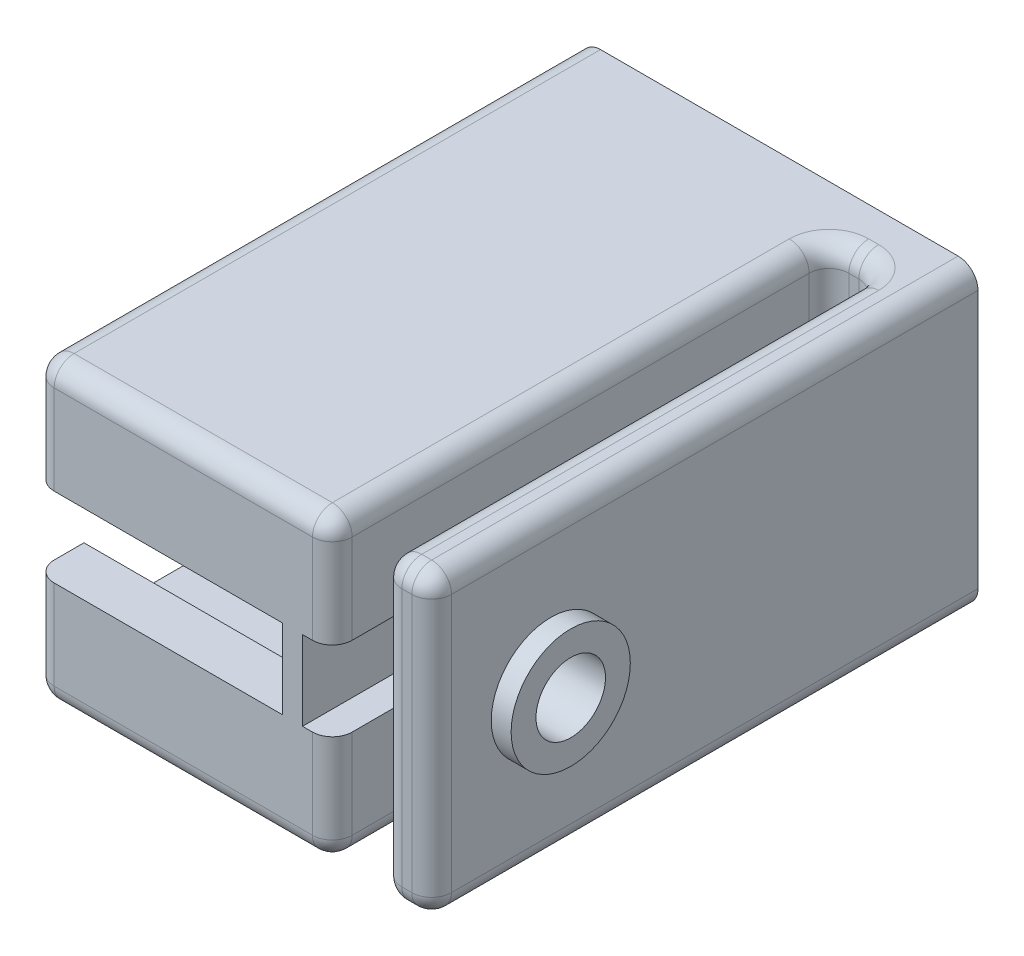
SolidWorks part; units mm, degrees
ref_plane "Plan de face" through (0, 0, 0) normal (0, 0, 1) x (1, 0, 0)
ref_plane "Plan de dessus" through (0, 0, 0) normal (0, 1, 0) x (1, 0, 0)
ref_plane "Plan de droite" through (0, 0, 0) normal (1, 0, 0) x (0, 0, -1)
sketch "Esquisse1" plane through (0, 0, 0) normal (0, 0, 1) x (1, 0, 0)
  line L0 (0, 0) -> (0, 15) construction
  line L1 (0, 0) -> (40, 0) construction
  line L3 (-20, -15) -> (20, -15)
  line L4 (-20, -15) -> (-20, 15)
  line L5 (-20, 15) -> (20, 15)
  line L6 (20, -15) -> (20, 15)
  point P8 (20, 0)
  dimension "D1" = 30
  dimension "D2" = 40
extrude "Boss.-Extru.1" add sketch "Esquisse1" along normal blind 5
sketch "Esquisse5" plane through (-20, 0, 0) normal (-1, 0, 0) x (0, 0, 1)
  line L0 (5, 15) -> (55, 15)
  line L1 (55, 15) -> (55, -15)
  line L2 (55, -15) -> (5, -15)
  line L3 (5, 15) -> (5, -15)
  dimension "D1" = 50
extrude "Boss.-Extru.3" add sketch "Esquisse5" against normal blind 30
sketch "Esquisse6" plane through (-20, 0, 0) normal (-1, 0, 0) x (0, 0, 1)
  line L0 (5, -15) -> (5, 15) construction
  line L1 (5, -15) -> (5, 15) construction
  line L2 (50, 11) -> (50, 4)
  line L3 (50, -11) -> (5, -11)
  line L4 (5, -11) -> (5, 11)
  line L5 (5, 11) -> (50, 11)
  line L6 (0, 0) -> (55, 0) construction
  line L7 (0, 15) -> (0, -15) construction
  line L8 (55, -15) -> (55, 15) construction
  line L9 (27.5, 15) -> (27.5, -15) construction
  line L10 (55, 15) -> (0, 15) construction
  line L11 (55, -15) -> (0, -15) construction
  line L12 (50, 4) -> (55, 4)
  line L13 (55, 4) -> (55, -4)
  line L14 (55, -4) -> (50, -4)
  line L15 (50, -4) -> (50, -11)
  point P11 (5, 0)
  point P20 (27.5, 0)
  point P21 (27.5, -11)
  point P25 (55, 0)
  dimension "D1" = 22
  dimension "D2" = 8
extrude "Enlèv. mat.-Extru.1" cut sketch "Esquisse6" against normal blind 25 contours L2 L12 L13 L14 L15 L3 L4 L5
sketch "Esquisse7" plane through (-20, 0, 0) normal (-1, 0, 0) x (0, 0, 1)
  line L0 (0, 0) -> (5, 0) construction
  line L1 (0, 15) -> (0, -15) construction
  line L2 (5, -11) -> (5, 11) construction
  line L3 (2.5, 4) -> (2.5, -4) construction
  circle A0 centre (2.5, 4) radius 1.3509
  circle A1 centre (2.5, -4) radius 1.3509
  point P9 (2.5, 0)
  dimension "D1" = 8
hole_wizard "Chambrage pour tête cylindrique fendue M2.51" positions "Esquisse9" profile "Esquisse11" counterbore size "M2.5" standard "ISO"
sketch "Esquisse9" plane through (0, 0, 5) normal (0, 0, 1) x (1, 0, 0)
  point P0 (0, 0)
sketch "Esquisse11" plane through (0, 0, 5) normal (1, 0, 0) x (0, -1, 0)
  line L0 (0, 0) -> (0, 7.8112)
  line L1 (0, 7.8112) -> (1.35, 7)
  line L2 (1.35, 7) -> (1.35, 1.8)
  line L3 (1.35, 1.8) -> (2.75, 1.8)
  line L4 (2.75, 1.8) -> (2.75, 0)
  line L5 (2.75, 0) -> (0, 0)
  line L10 (0, 7.8112) -> (-1.35, 7) construction
  line L11 (0, -6.35) -> (0, 107.95) construction
  dimension "Diamètre du perçage" = 2.7
  dimension "Profondeur du perçage" = 7
  dimension "Diamètre du chambrage" = 5.5
  dimension "Profondeur du chambrage" = 1.8
  dimension "Angle de pointe" = 118
sketch "Esquisse14" plane through (0, 0, 55) normal (0, 0, 1) x (1, 0, 0)
  line L0 (0, 0) -> (24.8017, 0) construction
  line L2 (5, 4) -> (5, -4) construction
  line L3 (10, -15) -> (10, 15) construction
  line L4 (5, 4) -> (5, -4) construction
  line L5 (5, 4) -> (-20, 4) construction
  line L6 (10, 4) -> (7, 4)
  line L7 (10, 4) -> (10, -4)
  line L8 (10, -4) -> (7, -4)
  line L9 (7, 4) -> (7, -4)
  line L10 (5, -4) -> (-20, -4) construction
  dimension "D1" = 3
extrude "Enlèv. mat.-Extru.2" cut sketch "Esquisse14" against normal through all
hole_wizard "Dégagement M31" positions "Esquisse12" profile "Esquisse13" hole size "M3" standard "ISO"
sketch "Esquisse12" plane through (-20, 0, 0) normal (-1, 0, 0) x (0, 0, 1)
  point P0 (2.5, -4)
  point P3 (2.5, 4)
sketch "Esquisse13" plane through (-20, -4, 2.5) normal (0, 1, 0) x (0, 0, 1)
  line L0 (0, 0) -> (0, 7.9614)
  line L1 (0, 7.9614) -> (1.6, 7)
  line L2 (1.6, 7) -> (1.6, 0)
  line L5 (1.6, 0) -> (0, 0)
  line L10 (0, 7.9614) -> (-1.6, 7) construction
  line L11 (0, -6.35) -> (0, 107.95) construction
  dimension "Diamètre du perçage" = 3.2
  dimension "Profondeur du perçage" = 7
  dimension "Angle de pointe" = 118
sketch "Esquisse16" plane through (20, 0, 0) normal (1, 0, 0) x (0, 0, -1)
  line L0 (0, 0) -> (-55, 0) construction
  line L1 (0, -15) -> (0, 15) construction
  line L2 (-55, 4) -> (-55, -4) construction
  line L3 (-5, -15) -> (-5, 15) construction
  line L4 (-5, -15) -> (-55, -15) construction
  line L5 (-55, 15) -> (-5, 15) construction
  line L6 (-55, -15) -> (-55, -4) construction
  line L7 (-5, -15) -> (-5, 15)
  line L8 (-5, -15) -> (-55, -15)
  line L9 (-55, 15) -> (-5, 15)
  line L10 (-55, -15) -> (-55, 15)
  circle A0 centre (-43, 0) radius 3.5
  dimension "D1" = 7
  dimension "D2" = 12
extrude "Boss.-Extru.4" add sketch "Esquisse16" against normal blind 5
fillet "Congé1" radius 2 23 edges at (12.5, 15, 5) (12.5, -15, 5) (20, -15, 27.5) (20, 15, 27.5) (-20, -15, 27.5) (-20, 15, 27.5) (-20, 9.5, 55) (-20, -9.5, 55) (10, 9.5, 5) (10, -9.5, 5) (-5, 15, 55) (10, 15, 30) (-5, -15, 55) (10, -15, 30) (10, 9.5, 55) (10, -9.5, 55) (17.5, -15, 55) (15, 0, 55) (17.5, 15, 55) (20, 0, 55) (15, 0, 5) (15, 15, 30) (15, -15, 30)
sketch "Esquisse17" plane through (15, 0, 0) normal (-1, 0, 0) x (0, 0, 1)
  line L0 (0, 0) -> (55, 0) construction
  line L1 (55, 13) -> (55, -13) construction
  line L3 (38, -5) -> (48, -5)
  line L4 (38, -5) -> (38, 5)
  line L5 (38, 5) -> (48, 5)
  line L6 (48, -5) -> (48, 5)
  line L7 (38, -5) -> (48, 5) construction
  line L8 (38, 5) -> (48, -5) construction
  circle A0 centre (43, 0) radius 3.5 construction
  circle A1 centre (43, 0) radius 3.5 construction
  dimension "D1" = 10
extrude "Enlèv. mat.-Extru.3" cut sketch "Esquisse17" against normal blind 2
sketch "Esquisse18" plane through (20, 0, 0) normal (1, 0, 0) x (0, 0, -1)
  line L0 (0, 0) -> (-53, 0) construction
  line L1 (0, -13) -> (0, 13) construction
  line L2 (-53, 13) -> (-53, -13) construction
  circle A0 centre (-43, 0) radius 3.5 construction
  circle A1 centre (-43, 0) radius 3.5
  circle A2 centre (-43, 0) radius 6
  dimension "D1" = 12
extrude "Boss.-Extru.5" add sketch "Esquisse18" along normal blind 2
